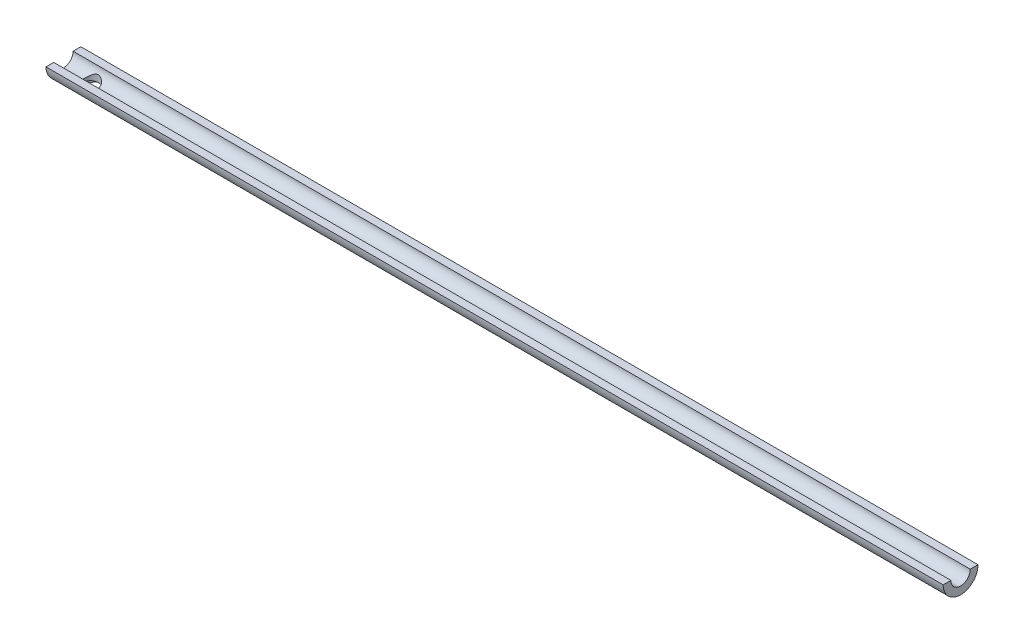
SolidWorks part; units mm, degrees
ref_plane "Front Plane" through (0, 0, 0) normal (0, 0, 1) x (1, 0, 0)
ref_plane "Top Plane" through (0, 0, 0) normal (0, 1, 0) x (1, 0, 0)
ref_plane "Right Plane" through (0, 0, 0) normal (1, 0, 0) x (0, 0, -1)
sketch "Sketch1" plane through (0, 0, 0) normal (0, 1, 0) x (1, 0, 0)
  line L1 (0, 0) -> (735.584, 0)
  line L2 (0, 0) -> (0, 38.1)
  line L3 (0, 38.1) -> (735.584, 38.1)
  line L4 (735.584, 0) -> (735.584, 38.1)
  dimension "D1" = 735.584
  dimension "D2" = 38.1
extrude "wood block" add sketch "Sketch1" along normal blind 15.875
sketch "Sketch2" plane through (735.584, 0, 0) normal (1, 0, 0) x (0, 0, -1)
  line L0 (0, 15.875) -> (38.1, 15.875) construction
  circle A0 centre (19.05, 15.875) radius 7.9375
  dimension "D1" = 15.875
extrude "inner bore" cut sketch "Sketch2" against normal through all
sketch "Sketch3" plane through (0, 0, 0) normal (0, 1, 0) x (1, 0, 0)
  line L0 (0, 19.05) -> (22.225, 19.05) construction
  line L1 (0, 26.9875) -> (0, 11.1125) construction
  circle A0 centre (22.225, 19.05) radius 6.35
  point P3 (15.875, 19.05)
  dimension "D1" = 12.7
  dimension "D2" = 15.875
extrude "mouthpiece through hole" cut sketch "Sketch3" along normal through all
sketch "Sketch5" plane through (0, 0, 0) normal (0, -1, 0) x (1, 0, 0)
  circle A0 centre (22.225, -19.05) radius 8.128
  dimension "D1" = 16.256
extrude "Cut-Extrude3" cut sketch "Sketch5" against normal blind 5.5499
sketch "Sketch4" plane through (0, 0, 0) normal (-1, 0, 0) x (0, 0, 1)
  circle A0 centre (-19.05, 15.875) radius 14.2875
  arc A1 (-26.9875, 15.875) -> (-11.1125, 15.875) centre (-19.05, 15.875) ccw construction
  dimension "D1" = 28.575
extrude "outer diameter" cut sketch "Sketch4" against normal through all flip side to cut
